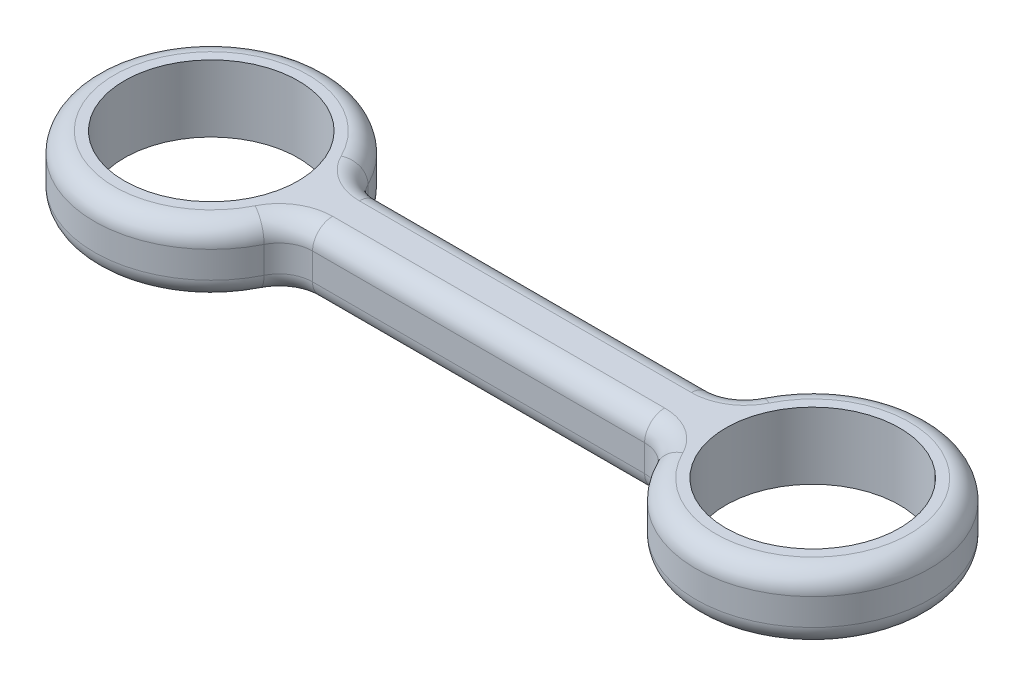
SolidWorks part; units mm, degrees
ref_plane "Front Plane" through (0, 0, 0) normal (0, 0, 1) x (1, 0, 0)
ref_plane "Top Plane" through (0, 0, 0) normal (0, 1, 0) x (1, 0, 0)
ref_plane "Right Plane" through (0, 0, 0) normal (1, 0, 0) x (0, 0, -1)
sketch "Sketch1" plane through (0, 0, 0) normal (0, 1, 0) x (1, 0, 0)
  line L0 (0, 0) -> (90, 0) construction
  line L3 (16.7705, 5) -> (73.2295, 5)
  line L4 (16.7705, -5) -> (73.2295, -5)
  circle A0 centre (0, 0) radius 13
  circle A1 centre (90, 0) radius 13
  arc A4 (16.7705, 5) -> (16.7705, -5) centre (0, 0) ccw
  arc A5 (73.2295, -5) -> (73.2295, 5) centre (90, 0) ccw
  dimension "D2" = 26
  dimension "D3" = 26
  dimension "D4" = 35
  dimension "D5" = 35
  dimension "D1" = 90
  dimension "D6" = 5
  dimension "D7" = 5
extrude "Boss-Extrude1" add sketch "Sketch1" along normal mid plane 10
fillet "Fillet1" radius 5 4 edges at (73.2295, 0, 5) (73.2295, 0, -5) (16.7705, 0, -5) (16.7705, 0, 5)
fillet "Fillet2" radius 3 16 edges at (17.5204, -5, 5.7508) (-17.5, -5, 0) (17.5204, -5, -5.7508) (45, -5, -5) (72.4796, -5, -5.7508) (107.5, -5, 0) (72.4796, -5, 5.7508) (17.5204, 5, 5.7508) (-17.5, 5, 0) (17.5204, 5, -5.7508) (45, 5, -5) (72.4796, 5, -5.7508) (107.5, 5, 0) (72.4796, 5, 5.7508) (45, -5, 5) (45, 5, 5)
